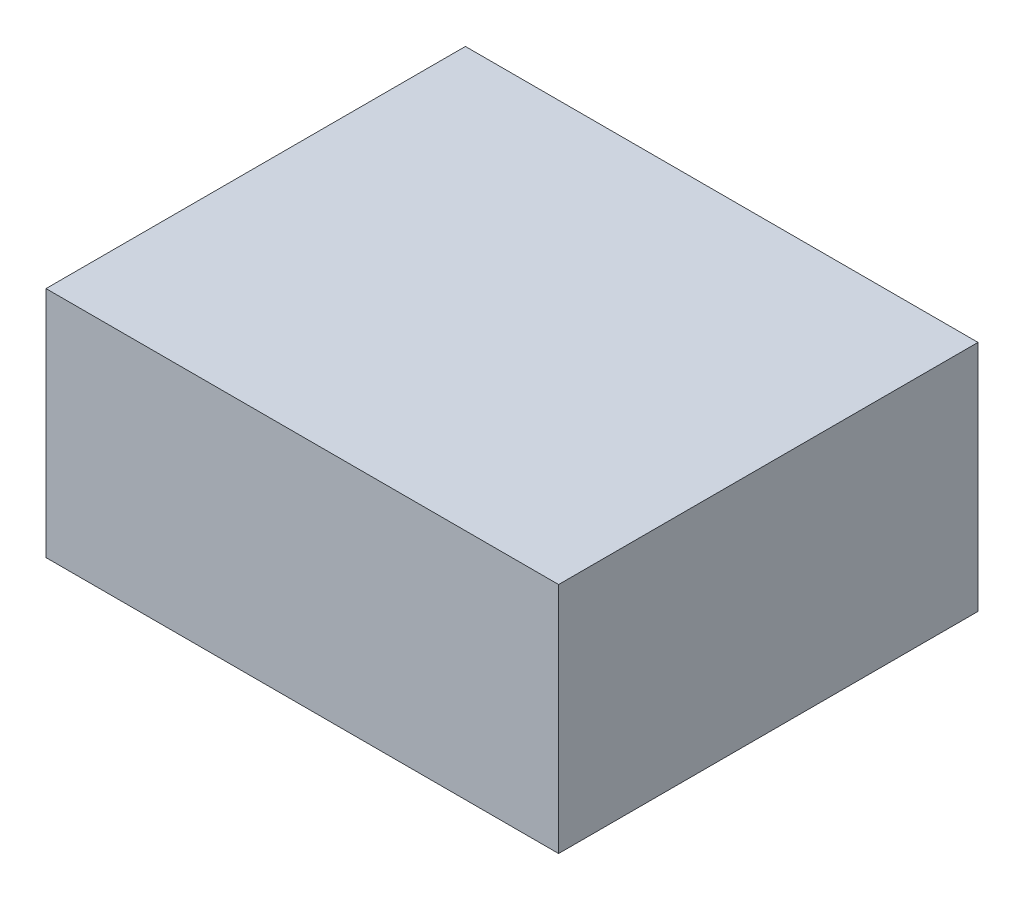
SolidWorks part; units mm, degrees
ref_plane "Front" through (0, 0, 0) normal (0, 0, 1) x (1, 0, 0)
ref_plane "Top" through (0, 0, 0) normal (0, 1, 0) x (1, 0, 0)
ref_plane "Right" through (0, 0, 0) normal (1, 0, 0) x (0, 0, -1)
sketch "Sketch1" plane through (0, 0, 0) normal (0, 1, 0) x (1, 0, 0)
  line L1 (0, 0) -> (69.85, 0)
  line L2 (0, 0) -> (0, 57.15)
  line L3 (0, 57.15) -> (69.85, 57.15)
  line L4 (69.85, 0) -> (69.85, 57.15)
  dimension "D1" = 57.15
  dimension "D2" = 69.85
extrude "Boss-Extrude1" add sketch "Sketch1" along normal blind 31.75 contours L3 L4 L1 L2
